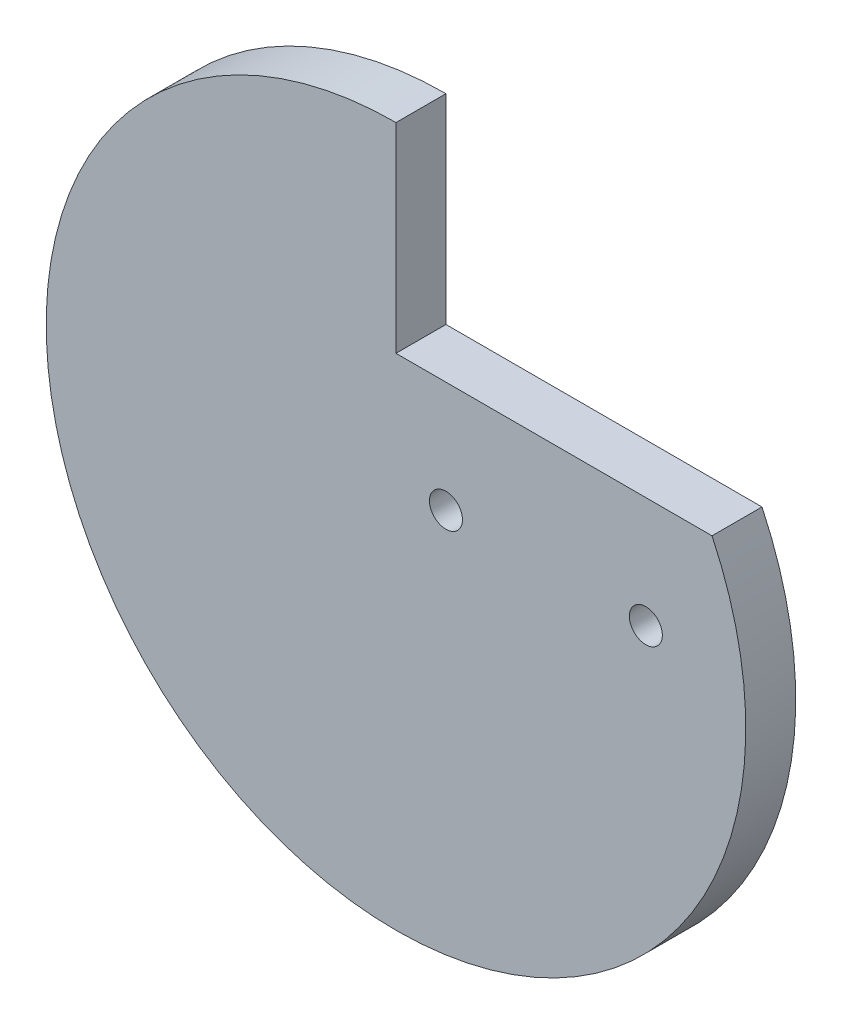
SolidWorks part; units mm, degrees
ref_plane "Front Plane" through (0, 0, 0) normal (0, 0, 1) x (1, 0, 0)
ref_plane "Top Plane" through (0, 0, 0) normal (0, 1, 0) x (1, 0, 0)
ref_plane "Right Plane" through (0, 0, 0) normal (1, 0, 0) x (0, 0, -1)
sketch "Sketch2" plane through (0, 0, 0) normal (0, 0, 1) x (1, 0, 0)
  circle A0 centre (0, 0) radius 35
  dimension "D1" = 70
extrude "Boss-Extrude1" add sketch "Sketch2" along normal blind 5
sketch "Sketch4" plane through (0, 0, 5) normal (0, 0, 1) x (1, 0, 0)
  line L0 (2.75, 0) -> (-2.75, 0) construction
  line L1 (0, 35) -> (60, 35)
  line L2 (0, 35) -> (0, 15)
  line L3 (0, 15) -> (60, 15)
  line L4 (60, 35) -> (60, 15)
  line L5 (2.3274, 1.1595) -> (10.8798, 1.1595) construction
  line L6 (0, -9.35) -> (0, 9.35) construction
  circle A0 centre (0, 0) radius 35 construction
  circle A1 centre (5, 3.9) radius 1.65
  circle A2 centre (25, 3.9) radius 1.65
  point P16 (12.0083, -3.3096)
  dimension "D3" = 3.3
  dimension "D4" = 3.3
  dimension "D1" = 15
  dimension "D2" = 20
  dimension "D5" = 0
  dimension "D6" = 3.9
  dimension "D7" = 5
  dimension "D8" = 60
extrude "Cut-Extrude1" cut sketch "Sketch4" against normal blind 5 contours A1 | A2 | L4 L3 L2 L1
